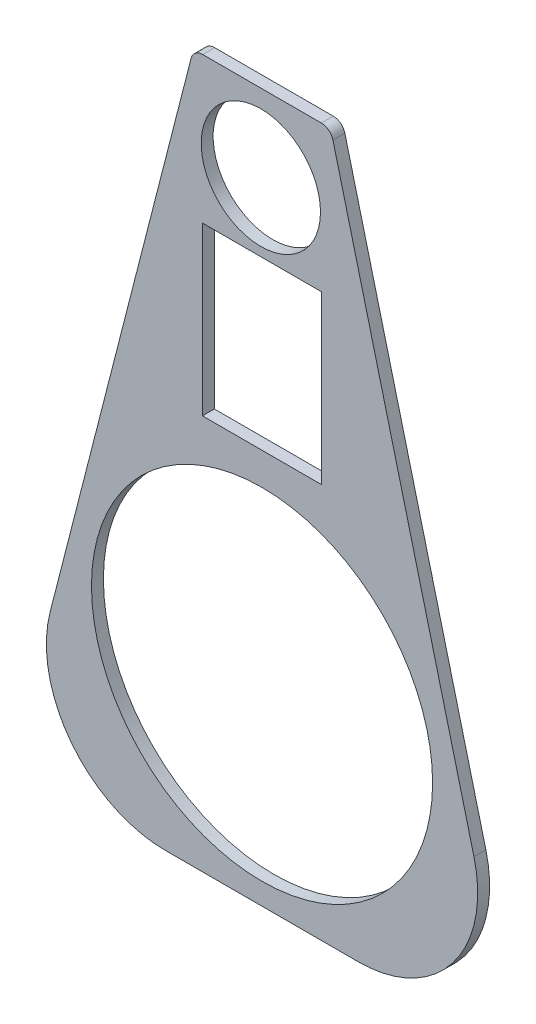
SolidWorks part; units mm, degrees
material "6061 Alloy"
ref_plane "Front" through (0, 0, 0) normal (0, 0, 1) x (1, 0, 0)
ref_plane "Top" through (0, 0, 0) normal (0, 1, 0) x (1, 0, 0)
ref_plane "Right" through (0, 0, 0) normal (1, 0, 0) x (0, 0, -1)
sketch "Sketch3" plane through (0, 0, 0) normal (0, 0, 1) x (1, 0, 0)
  line L1 (953.6997, -1070.1047) -> (362.5166, 1235.9362)
  line L3 (-231.8855, 1235.9362) -> (-823.0686, -1070.1047)
  line L4 (65.3155, 1273.5196) -> (65.3155, -1694.2708) construction
  line L17 (-183.4518, 1273.5196) -> (314.0829, 1273.5196)
  line L19 (-184.6845, -38.8919) -> (315.3155, -38.8919)
  line L20 (-184.6845, -38.8919) -> (-184.6845, 661.1081)
  line L21 (-184.6845, 661.1081) -> (315.3155, 661.1081)
  line L22 (315.3155, -38.8919) -> (315.3155, 661.1081)
  line L23 (-338.7311, -1694.2708) -> (469.3622, -1694.2708)
  line L24 (-184.6845, -38.8919) -> (315.3155, 661.1081) construction
  line L25 (-184.6845, 661.1081) -> (315.3155, -38.8919) construction
  arc A10 (-231.8855, 1235.9362) -> (-183.4518, 1273.5196) centre (-183.4518, 1223.5196) cw
  arc A11 (362.5166, 1235.9362) -> (314.0829, 1273.5196) centre (314.0829, 1223.5196) ccw
  circle A13 centre (60.2947, 948.3527) radius 250
  circle A14 centre (65.3155, -888.8919) radius 715
  arc A15 (-823.0686, -1070.1047) -> (-338.7311, -1694.2708) centre (-338.7311, -1194.2708) ccw
  arc A16 (469.3622, -1694.2708) -> (953.6997, -1070.1047) centre (469.3622, -1194.2708) ccw
  point P1 (65.3155, 311.1081)
  point P11 (60.2939, 331.5151)
  point P28 (-222.2506, 1273.5196)
  point P33 (352.8817, 1273.5196)
  dimension "D4" = 500
  dimension "D5" = 700
  dimension "D6" = 500
  dimension "D7" = 500
  dimension "D8" = 500
  dimension "D9" = 50
  dimension "D11" = 50
  dimension "D2" = 1430
  dimension "D3" = 1200
extrude "Boss-Extrude1" add sketch "Sketch3" along normal blind 50
